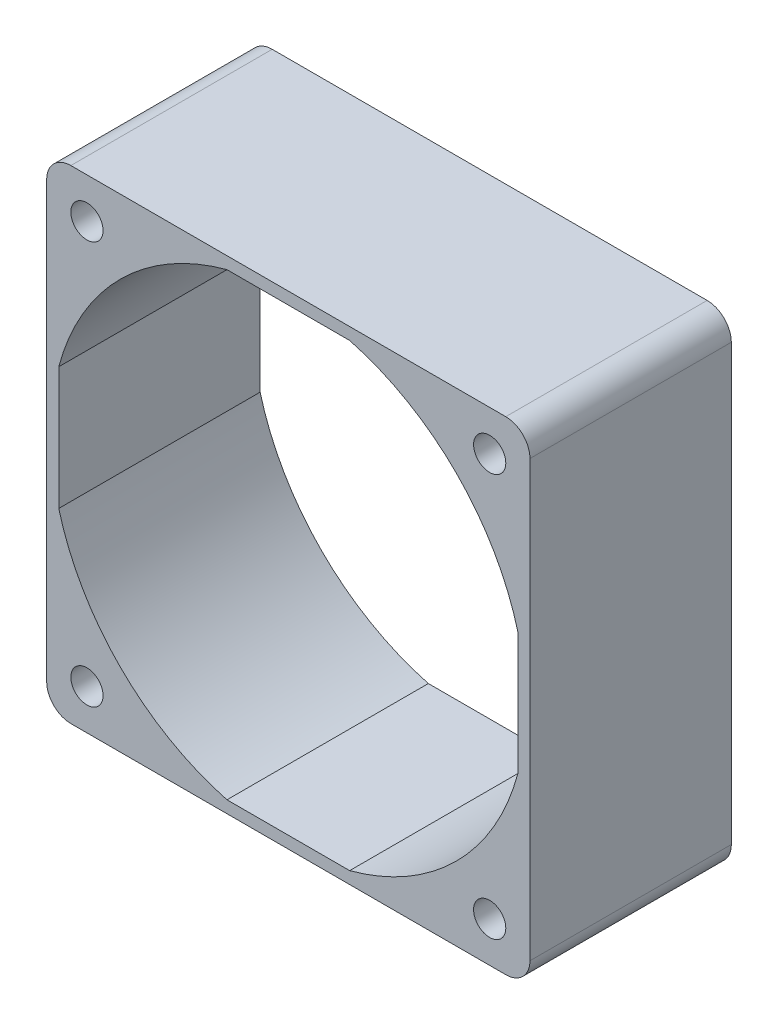
SolidWorks part; units mm, degrees
ref_plane "Front Plane" through (0, 0, 0) normal (0, 0, 1) x (1, 0, 0)
ref_plane "Top Plane" through (0, 0, 0) normal (0, 1, 0) x (1, 0, 0)
ref_plane "Right Plane" through (0, 0, 0) normal (1, 0, 0) x (0, 0, -1)
sketch "Sketch1" plane through (0, 0, 0) normal (0, 0, 1) x (1, 0, 0)
  line L1 (-27, 30) -> (27, 30)
  line L2 (-30, 27) -> (-30, -27)
  line L3 (-27, -30) -> (27, -30)
  line L4 (30, 27) -> (30, -27)
  line L5 (-7.6158, 28.5) -> (7.6158, 28.5)
  line L6 (-28.5, 7.6158) -> (-28.5, -7.6158)
  line L7 (-7.6158, -28.5) -> (7.6158, -28.5)
  line L8 (28.5, 7.6158) -> (28.5, -7.6158)
  line L9 (-25, 25) -> (25, 25) construction
  line L10 (-25, 25) -> (-25, -25) construction
  line L11 (-25, -25) -> (25, -25) construction
  line L12 (25, 25) -> (25, -25) construction
  arc A0 (-7.6158, 28.5) -> (-28.5, 7.6158) centre (0, 0) ccw
  arc A1 (28.5, 7.6158) -> (7.6158, 28.5) centre (0, 0) ccw
  arc A2 (7.6158, -28.5) -> (28.5, -7.6158) centre (0, 0) ccw
  arc A3 (-28.5, -7.6158) -> (-7.6158, -28.5) centre (0, 0) ccw
  circle A4 centre (-25, 25) radius 2
  circle A5 centre (25, 25) radius 2
  circle A6 centre (25, -25) radius 2
  circle A7 centre (-25, -25) radius 2
  arc A8 (-27, -30) -> (-30, -27) centre (-27, -27) cw
  arc A9 (27, -30) -> (30, -27) centre (27, -27) ccw
  arc A10 (30, 27) -> (27, 30) centre (27, 27) ccw
  arc A11 (-27, 30) -> (-30, 27) centre (-27, 27) ccw
  point P7 (0, 30)
  point P8 (0, 28.5)
  point P9 (30, 0)
  point P14 (28.5, 0)
  point P34 (0, 25)
  point P35 (-25, 0)
  point P36 (-30, 0)
  point P37 (0, 0)
  point P38 (0, 0)
  point P39 (0, 0)
  point P40 (0, 0)
  point P43 (30, 30)
  point P46 (-30, 30)
  dimension "D2" = 59
  dimension "D6" = 4
  dimension "D3" = 3
  dimension "D1" = 60
  dimension "D4" = 50
  dimension "D5" = 50
extrude "Boss-Extrude1" add sketch "Sketch1" along normal blind 25
